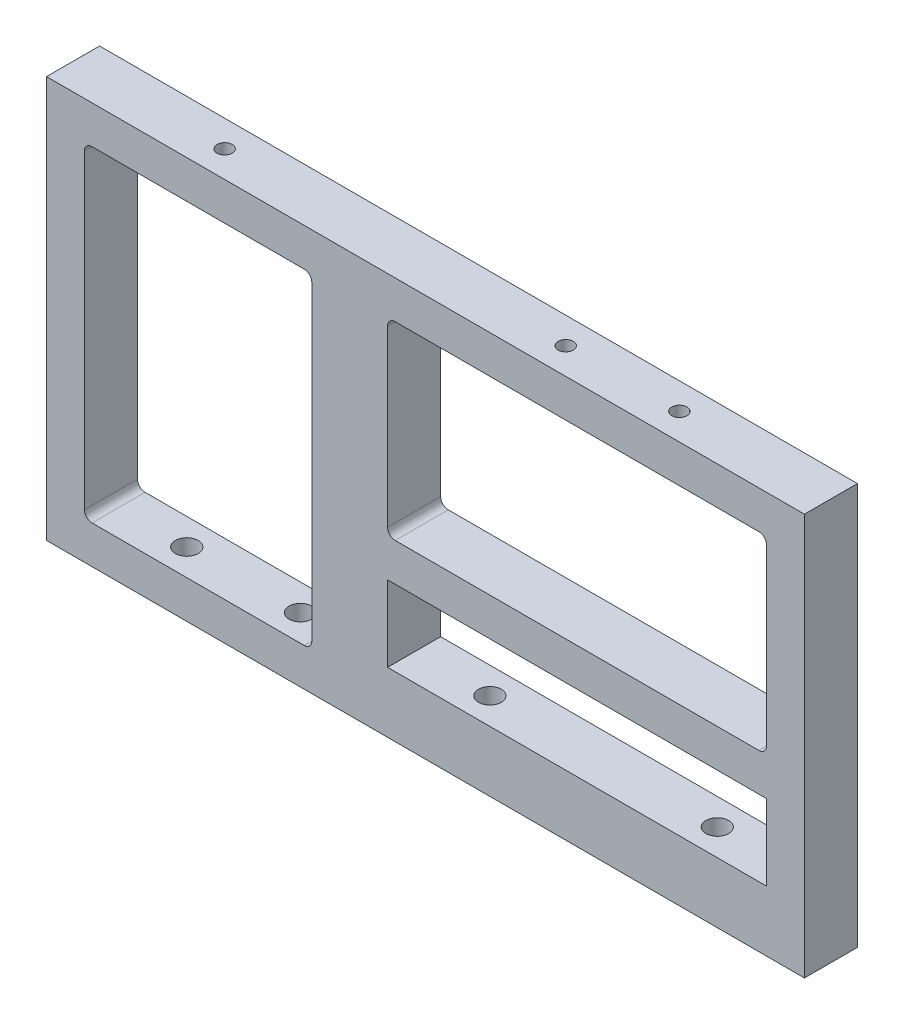
SolidWorks part; units mm, degrees
ref_plane "前视基准面" through (0, 0, 0) normal (0, 0, 1) x (1, 0, 0)
ref_plane "上视基准面" through (0, 0, 0) normal (0, 1, 0) x (1, 0, 0)
ref_plane "右视基准面" through (0, 0, 0) normal (1, 0, 0) x (0, 0, -1)
other "Configuration Table"
sketch "草图1" plane through (0, 0, 0) normal (0, 0, 1) x (1, 0, 0)
  line L0 (0, 0) -> (100, 0)
  line L1 (100, 0) -> (100, 53)
  line L2 (100, 53) -> (0, 53)
  line L3 (0, 53) -> (0, 0)
  line L8 (5, 48) -> (5, 5)
  line L9 (5, 5) -> (35, 5)
  line L10 (35, 5) -> (35, 48)
  line L11 (35, 48) -> (5, 48)
  line L12 (45, 48) -> (45, 23)
  line L17 (45, 8) -> (95, 8)
  line L18 (95, 8) -> (95, 18)
  line L19 (95, 48) -> (45, 48)
  line L20 (45, 23) -> (95, 23)
  line L21 (45, 18) -> (95, 18)
  line L22 (45, 18) -> (45, 8)
  line L23 (95, 23) -> (95, 48)
  dimension "D1" = 100
  dimension "D2" = 53
  dimension "D3" = 43
  dimension "D4" = 5
  dimension "D5" = 30
  dimension "D6" = 5
  dimension "D7" = 5
  dimension "D8" = 10
  dimension "D9" = 50
  dimension "D10" = 40
  dimension "D11" = 5
  dimension "D12" = 10
extrude "凸台-拉伸1" add sketch "草图1" along normal blind 7
fillet "圆角1" radius 1 8 edges at (95, 23, 3.5) (95, 48, 3.5) (45, 23, 3.5) (45, 48, 3.5) (35, 48, 3.5) (35, 5, 3.5) (5, 5, 3.5) (5, 48, 3.5)
sketch "草图2" plane through (0, 0, 0) normal (0, -1, 0) x (1, 0, 0)
  line L3 (0, 0) -> (100, 0) construction
  line L5 (0, 7) -> (0, 0) construction
  circle A0 centre (15, 3.5) radius 1.5
  circle A1 centre (85, 3.5) radius 1.5
  circle A2 centre (55, 3.5) radius 1.5
  circle A3 centre (30, 3.5) radius 1.5
  dimension "D1" = 3
  dimension "D2" = 3
  dimension "D3" = 3
  dimension "D5" = 3
  dimension "D4" = 3.5
  dimension "D6" = 15
  dimension "D7" = 30
  dimension "D8" = 25
  dimension "D9" = 15
extrude "切除-拉伸2" cut sketch "草图2" against normal up to next
sketch "草图3" plane through (0, 53, 0) normal (0, 1, 0) x (1, 0, 0)
  circle A1 centre (80, -3.5) radius 1
  circle A2 centre (65, -3.5) radius 1
  circle A4 centre (20, -3.5) radius 1
  dimension "D1" = 2
  dimension "D2" = 2
  dimension "D3" = 2
extrude "切除-拉伸3" cut sketch "草图3" against normal blind 5
